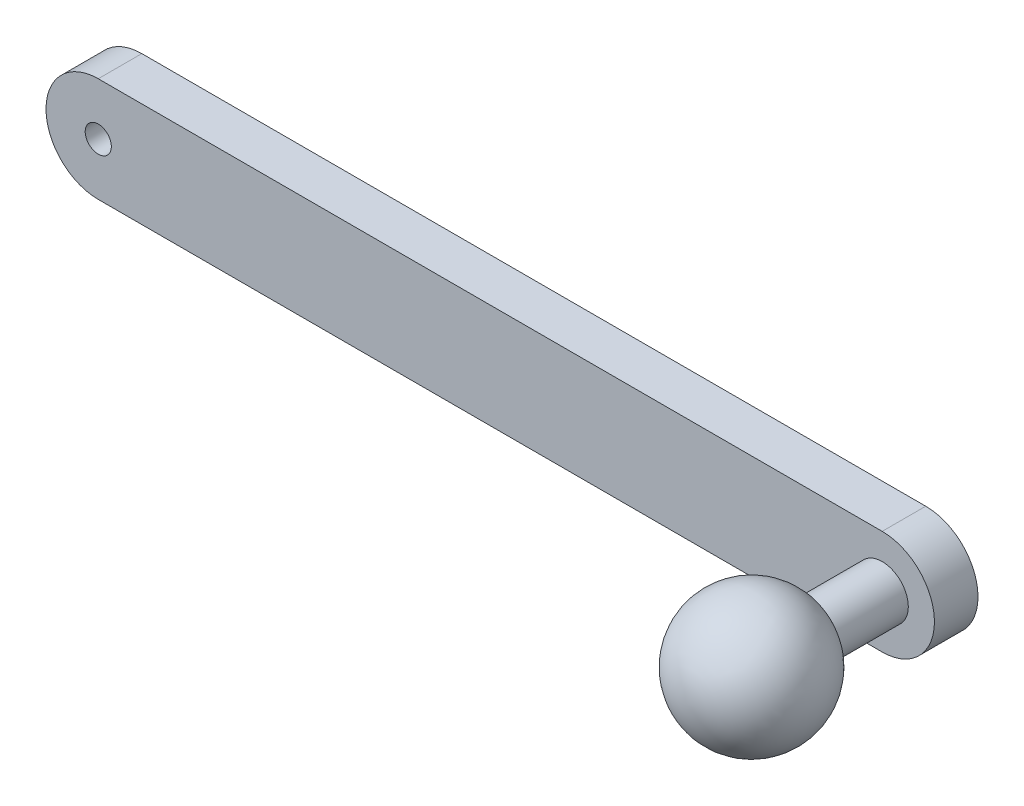
SolidWorks part; units mm, degrees
ref_plane "Front Plane" through (0, 0, 0) normal (0, 0, 1) x (1, 0, 0)
ref_plane "Top Plane" through (0, 0, 0) normal (0, 1, 0) x (1, 0, 0)
ref_plane "Right Plane" through (0, 0, 0) normal (1, 0, 0) x (0, 0, -1)
sketch "Sketch1" plane through (0, 0, 0) normal (0, 0, 1) x (1, 0, 0)
  line L0 (0, 0) -> (90, 0) construction
  line L1 (0, 6) -> (90, 6)
  line L2 (0, -6) -> (90, -6)
  circle A0 centre (0, 0) radius 1.5
  circle A1 centre (90, 0) radius 1.5
  circle A2 centre (0, 0) radius 6
  circle A3 centre (90, 0) radius 6
  dimension "D2" = 3
  dimension "D3" = 3
  dimension "D4" = 12
  dimension "D5" = 12
  dimension "D1" = 90
extrude "Boss-Extrude1" add sketch "Sketch1" along normal blind 5
fillet "Fillet3" radius 1 1 edges at (91.5, 0, 0)
sketch "Sketch2" plane through (0, 0, 5) normal (0, 0, 1) x (1, 0, 0)
  circle A0 centre (90, 0) radius 3
extrude "Boss-Extrude2" add sketch "Sketch2" along normal blind 20 from offset 5 offset against normal yes
sketch "Sketch3" plane through (0, 0, 20) normal (0, 0, 1) x (1, 0, 0)
  line L0 (82.5, 0) -> (97.5, 0)
  line L1 (90, 0) -> (97.2814, 0) construction
  arc A0 (97.5, 0) -> (82.5, 0) centre (90, 0) ccw
revolve "Revolve1" add sketch "Sketch3" angle 360 about L1
